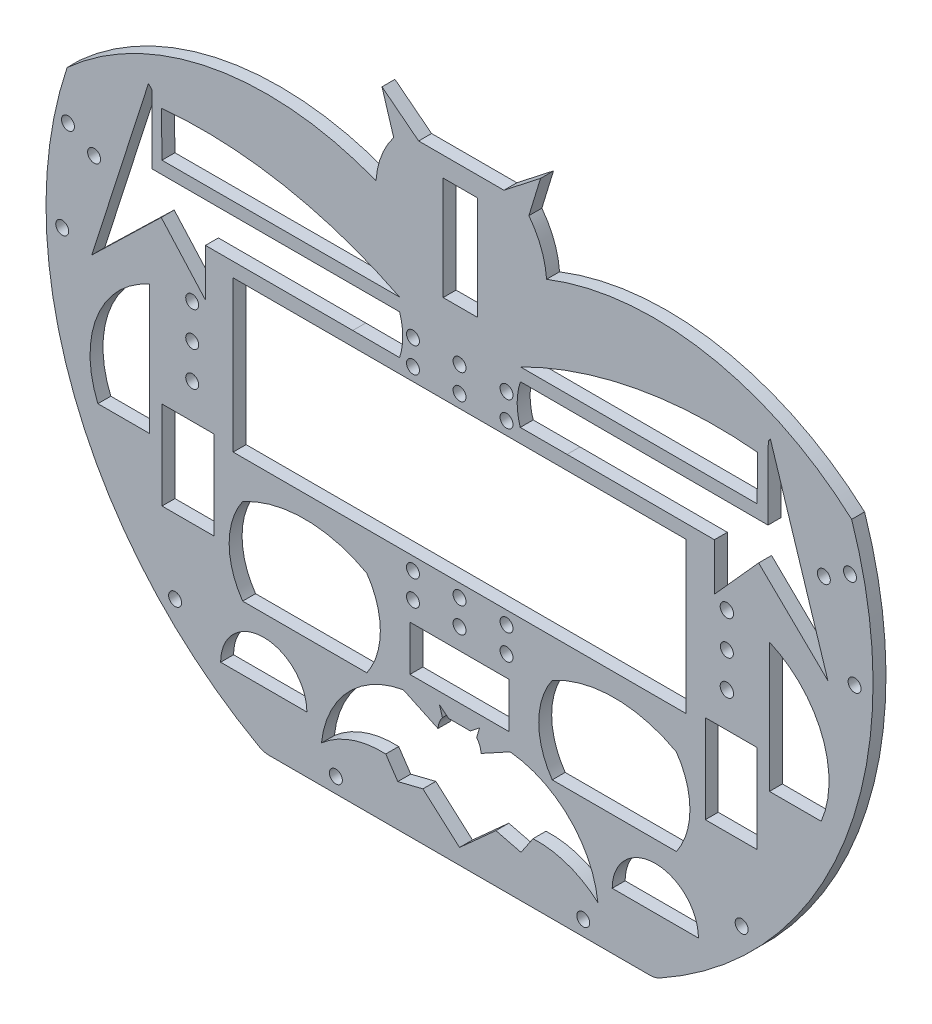
SolidWorks part; units mm, degrees
material "MDF"
ref_plane "Alzado" through (0, 0, 0) normal (0, 0, 1) x (1, 0, 0)
ref_plane "Planta" through (0, 0, 0) normal (0, 1, 0) x (1, 0, 0)
ref_plane "Vista lateral" through (0, 0, 0) normal (1, 0, 0) x (0, 0, -1)
sketch "Model" plane through (0, 0, 0) normal (0, 0, 1) x (1, 0, 0)
  line L109 (-383.5643, -10.2122) -> (-383.5643, 19.7878)
  line L110 (-383.5643, -10.2122) -> (-395.5643, -10.2122)
  line L111 (-239.8116, -10.2122) -> (-227.8116, -10.2122)
  line L112 (-239.8116, -10.2122) -> (-239.8116, 19.7878)
  line L113 (-240.1446, 43.1032) -> (-297.5673, 43.1999)
  line L114 (-240.0881, 60.0466) -> (-240.1446, 43.1032)
  line L115 (-240.0881, 60.0466) -> (-239.5883, 60.6681)
  line L116 (-226.251, 18.7933) -> (-239.5883, 60.6681)
  line L117 (-242.3246, 34.4242) -> (-226.251, 18.7933)
  line L118 (-252.5961, 22.9824) -> (-242.3246, 34.4242)
  line L119 (-252.5777, 33.9538) -> (-252.5961, 22.9824)
  line L120 (-286.7519, 34.0113) -> (-252.5777, 33.9538)
  line L121 (-297.6022, 34.0019) -> (-286.7519, 34.0113)
  line L122 (-325.5945, 34.0254) -> (-336.4448, 34.0531)
  line L123 (-336.4448, 34.0531) -> (-370.6191, 34.0531)
  line L124 (-370.6191, 34.0531) -> (-370.6191, 23.0817)
  line L125 (-370.6191, 23.0817) -> (-380.8714, 34.5408)
  line L126 (-380.8714, 34.5408) -> (-396.9712, 18.937)
  line L127 (-396.9712, 18.937) -> (-383.8241, 59.9758)
  line L128 (-383.063, 59.1251) -> (-383.8241, 59.9758)
  line L129 (-383.063, 59.1251) -> (-383.0368, 43.2235)
  line L130 (-325.5945, 43.2235) -> (-383.0368, 43.2235)
  line L131 (-256.2813, -47.905) -> (-276.2813, -47.905)
  line L132 (-367.0945, -47.905) -> (-347.0945, -47.905)
  line L133 (-261.3879, -33.0842) -> (-290.1879, -33.0842)
  line L134 (-333.1879, -33.0842) -> (-361.9879, -33.0842)
  line L135 (-306.6879, -36.0265) -> (-299.9347, -32.3317)
  line L136 (-297.4347, -51.2649) -> (-294.6388, -47.1197)
  line L137 (-303.2565, -49.8134) -> (-297.4347, -51.2649)
  line L138 (-311.6879, -57.405) -> (-303.2565, -49.8134)
  line L139 (-311.6879, -57.405) -> (-320.1803, -49.8816)
  line L140 (-320.1803, -49.8816) -> (-326.0021, -51.3332)
  line L141 (-326.0021, -51.3332) -> (-328.7981, -47.188)
  line L142 (-316.6879, -36.0265) -> (-324.7201, -32.2631)
  line L143 (-316.3346, -31.0798) -> (-315.651, -33.3158)
  line L144 (-314.1879, -32.757) -> (-316.3346, -31.0798)
  line L145 (-309.1879, -32.757) -> (-314.1879, -32.757)
  line L146 (-309.1879, -32.757) -> (-307.0412, -31.0798)
  line L147 (-307.0412, -31.0798) -> (-307.7248, -33.3158)
  line L148 (-242.6729, 46.1178) -> (-297.5673, 46.1798)
  line L149 (-242.6729, 46.1178) -> (-242.5645, 56.5162)
  line L150 (-323.1879, -17.905) -> (-323.1879, -28.405)
  line L151 (-323.1879, -17.905) -> (-300.1879, -17.905)
  line L152 (-300.1879, -17.905) -> (-300.1879, -28.405)
  line L153 (-323.1879, -28.405) -> (-300.1879, -28.405)
  line L154 (-254.6879, -23.3342) -> (-254.6879, -2.8342)
  line L155 (-254.6879, -2.8342) -> (-242.6879, -2.8342)
  line L156 (-242.6879, -23.3342) -> (-242.6879, -2.8342)
  line L157 (-242.6879, -23.3342) -> (-254.6879, -23.3342)
  line L158 (-380.6879, -2.8342) -> (-380.6879, -23.3342)
  line L159 (-368.6879, -2.8342) -> (-380.6879, -2.8342)
  line L160 (-368.6879, -23.3342) -> (-368.6879, -2.8342)
  line L161 (-380.6879, -23.3342) -> (-368.6879, -23.3342)
  line L162 (-315.4882, 51.1384) -> (-307.4882, 51.1384)
  line L163 (-315.4882, 75.1384) -> (-315.4882, 51.1384)
  line L164 (-307.4882, 75.1384) -> (-315.4882, 75.1384)
  line L165 (-307.4882, 51.1384) -> (-307.4882, 75.1384)
  line L166 (-364.1879, -4.2485) -> (-259.1879, -4.2485)
  line L167 (-364.1879, -4.2485) -> (-364.1879, 30.7515)
  line L168 (-364.1879, 30.7515) -> (-259.1879, 30.7515)
  line L169 (-259.1879, -4.2485) -> (-259.1879, 30.7515)
  line L170 (-380.703, 46.1178) -> (-325.5945, 46.1798)
  line L171 (-380.703, 46.1178) -> (-380.8113, 56.5162)
  line L172 (-267.5998, -60.9985) -> (-355.776, -60.9985)
  line L173 (-311.2814, 79.7441) -> (-321.1734, 79.7441)
  line L174 (-311.2814, 79.7441) -> (-301.3894, 79.7441)
  line L175 (-301.3894, 79.7441) -> (-292.8954, 86.3804)
  line L176 (-292.8954, 86.3804) -> (-295.5918, 77.5609)
  line L177 (-292.8954, 86.3804) -> (-295.6004, 77.5329)
  line L178 (-321.1734, 79.7441) -> (-329.6674, 86.3804)
  line L179 (-329.6674, 86.3804) -> (-326.971, 77.5609)
  line L180 (-329.6674, 86.3804) -> (-326.9624, 77.5329)
  line L181 (-300.0064, 22.8853) -> (-311.4919, 22.8853)
  line L182 (-311.4919, 2.8853) -> (-268.5209, 2.8853)
  line L183 (-268.5209, 2.8853) -> (-268.5209, 22.8853)
  line L184 (-268.5209, 22.8853) -> (-280.0064, 22.8853)
  line L185 (-280.0064, 22.8853) -> (-300.0064, 22.8853)
  line L186 (-282.0064, 20.8853) -> (-298.03, 20.8853)
  line L187 (-298.03, 16.8853) -> (-282.0064, 16.8853)
  line L188 (-282.0064, 16.8853) -> (-282.0064, 20.8853)
  line L189 (-298.03, 16.8853) -> (-298.03, 20.8853)
  line L190 (-282.0064, 6.8853) -> (-282.0064, 4.8853)
  line L191 (-282.0064, 4.8853) -> (-298.0064, 4.8853)
  line L192 (-298.0064, 4.8853) -> (-298.0064, 8.8853)
  line L193 (-298.0064, 8.8853) -> (-282.0064, 8.8853)
  line L194 (-282.0064, 6.8853) -> (-282.0064, 8.8853)
  line L195 (-342.9774, 22.8853) -> (-354.4629, 22.8853)
  line L196 (-354.4629, 22.8853) -> (-354.4629, 2.8853)
  line L197 (-354.4629, 2.8853) -> (-311.4919, 2.8853)
  line L198 (-311.4919, 2.8853) -> (-311.4919, 22.8853)
  line L199 (-311.4919, 22.8853) -> (-322.9774, 22.8853)
  line L200 (-322.9774, 22.8853) -> (-342.9774, 22.8853)
  line L201 (-324.9774, 20.8853) -> (-341.001, 20.8853)
  line L202 (-341.001, 16.8853) -> (-324.9774, 16.8853)
  line L203 (-324.9774, 16.8853) -> (-324.9774, 20.8853)
  line L204 (-341.001, 16.8853) -> (-341.001, 20.8853)
  line L205 (-324.9774, 6.8853) -> (-324.9774, 4.8853)
  line L206 (-324.9774, 4.8853) -> (-340.9774, 4.8853)
  line L207 (-340.9774, 4.8853) -> (-340.9774, 8.8853)
  line L208 (-340.9774, 8.8853) -> (-324.9774, 8.8853)
  line L209 (-324.9774, 6.8853) -> (-324.9774, 8.8853)
  arc A148 (-383.5643, 19.7878) -> (-395.5643, -10.2122) centre (-374.4429, -1.2607) ccw
  arc A149 (-227.8116, -10.2122) -> (-239.8116, 19.7878) centre (-248.9329, -1.2607) ccw
  arc A150 (-297.5673, 43.1999) -> (-297.6022, 34.0019) centre (-283.6304, 38.5479) ccw
  arc A151 (-325.5945, 34.0254) -> (-325.5945, 43.2235) centre (-339.5587, 38.6245) ccw
  circle A152 centre (-403.8396, 21.0015) radius 1.5
  arc A153 (-256.2813, -47.905) -> (-276.2813, -47.905) centre (-266.2813, -47.905) ccw
  arc A154 (-347.0945, -47.905) -> (-367.0945, -47.905) centre (-357.0945, -47.905) ccw
  arc A155 (-261.3879, -13.0842) -> (-290.1879, -13.0842) centre (-275.7879, -39.204) ccw
  arc A156 (-261.3879, -33.0842) -> (-261.3879, -13.0842) centre (-275.7879, -23.0842) ccw
  arc A157 (-290.1879, -13.0842) -> (-290.1879, -33.0842) centre (-275.7879, -23.0842) ccw
  arc A158 (-333.1879, -13.0842) -> (-361.9879, -13.0842) centre (-347.5879, -39.204) ccw
  arc A159 (-333.1879, -33.0842) -> (-333.1879, -13.0842) centre (-347.5879, -23.0842) ccw
  arc A160 (-361.9879, -13.0842) -> (-361.9879, -33.0842) centre (-347.5879, -23.0842) ccw
  arc A161 (-306.6879, -36.0265) -> (-307.7248, -33.3158) centre (-311.6879, -36.3855) ccw
  arc A162 (-279.5945, -52.4477) -> (-299.9347, -32.3317) centre (-302.2093, -54.9731) ccw
  arc A163 (-279.5945, -52.4477) -> (-294.6388, -47.1197) centre (-293.6054, -68.1057) ccw
  arc A164 (-328.7981, -47.188) -> (-343.7213, -52.4477) centre (-329.7655, -68.2435) ccw
  arc A165 (-324.7201, -32.2631) -> (-343.7213, -52.4477) centre (-320.8173, -54.9731) ccw
  arc A166 (-315.651, -33.3158) -> (-316.6879, -36.0265) centre (-311.6879, -36.3855) ccw
  circle A167 centre (-300.7905, 33.7515) radius 1.5
  circle A168 centre (-311.6879, 33.7515) radius 1.5
  circle A169 centre (-322.4895, 33.7515) radius 1.5
  circle A170 centre (-300.7905, -7.2485) radius 1.5
  circle A171 centre (-322.4895, -7.2485) radius 1.5
  circle A172 centre (-311.6879, -7.2485) radius 1.5
  circle A173 centre (-300.7905, -13.0985) radius 1.5
  circle A174 centre (-311.6879, -13.0985) radius 1.5
  circle A175 centre (-322.4895, -13.0985) radius 1.5
  circle A176 centre (-311.6879, 39.6015) radius 1.5
  circle A177 centre (-246.259, -40.4985) radius 1.5
  circle A178 centre (-377.6551, -40.4985) radius 1.5
  circle A179 centre (-220.0744, 21.0015) radius 1.5
  circle A180 centre (-221.1355, 42.7751) radius 1.5
  circle A181 centre (-402.5081, 42.6625) radius 1.5
  circle A182 centre (-249.6879, 13.2515) radius 1.5
  circle A183 centre (-373.6879, 13.2515) radius 1.5
  circle A184 centre (-373.6879, 5.2515) radius 1.5
  circle A185 centre (-373.6879, 21.2515) radius 1.5
  circle A186 centre (-322.4895, 39.6015) radius 1.5
  arc A187 (-242.5645, 56.5162) -> (-297.5673, 46.1798) centre (-252.0932, -44.2895) ccw
  arc A188 (-325.5945, 46.1798) -> (-380.8113, 56.5162) centre (-371.2667, -45.148) ccw
  circle A189 centre (-300.7905, 39.6015) radius 1.5
  circle A190 centre (-249.6879, 5.2515) radius 1.55
  circle A191 centre (-249.6879, 21.2515) radius 1.55
  circle A192 centre (-340.3716, -57.4985) radius 1.5
  circle A193 centre (-283.004, -57.4985) radius 1.5
  circle A194 centre (-396.4459, 39.1625) radius 1.5
  circle A195 centre (-227.1977, 39.2751) radius 1.5
  arc A196 (-267.5998, -60.9985) -> (-265.1749, -60.3711) centre (-267.5998, -55.9985) ccw
  arc A197 (-265.1749, -60.3711) -> (-220.7464, 53.9601) centre (-311.6879, 23.5015) ccw
  arc A198 (-229.7037, 60.7704) -> (-230.2287, 60.7842) centre (-230.2287, 50.7842) ccw
  arc A199 (-393.2143, 60.5827) -> (-393.8028, 60.5654) centre (-393.2143, 50.5827) ccw
  arc A200 (-402.7044, 53.7351) -> (-358.2009, -60.3711) centre (-311.6879, 23.5015) ccw
  arc A201 (-358.2009, -60.3711) -> (-355.776, -60.9985) centre (-355.776, -55.9985) ccw
  arc A202 (-326.9624, 77.5329) -> (-331.0653, 66.807) centre (-311.2814, 65.3868) ccw
  arc A203 (-291.4975, 66.807) -> (-295.6004, 77.5329) centre (-311.2814, 65.3868) ccw
  arc A204 (-331.0653, 66.807) -> (-402.7044, 53.7351) centre (-356.3507, 2.5399) ccw
  arc A205 (-220.7464, 53.9601) -> (-291.4975, 66.807) centre (-266.5359, 3.0318) ccw
  circle A206 centre (-280.0064, 12.8853) radius 1.5
  circle A207 centre (-300.0064, 12.8853) radius 1.5
  circle A208 centre (-306.9847, 7.8853) radius 1.5
  circle A209 centre (-306.9847, 17.8853) radius 1.5
  circle A210 centre (-273.028, 17.8853) radius 1.5
  circle A211 centre (-273.028, 7.8853) radius 1.5
  circle A212 centre (-322.9774, 12.8853) radius 1.5
  circle A213 centre (-342.9774, 12.8853) radius 1.5
  circle A214 centre (-349.9557, 7.8853) radius 1.5
  circle A215 centre (-349.9557, 17.8853) radius 1.5
  circle A216 centre (-315.9991, 17.8853) radius 1.5
  circle A217 centre (-315.9991, 7.8853) radius 1.5
extrude "Saliente-Extruir4" add sketch "Model" along normal blind 3
